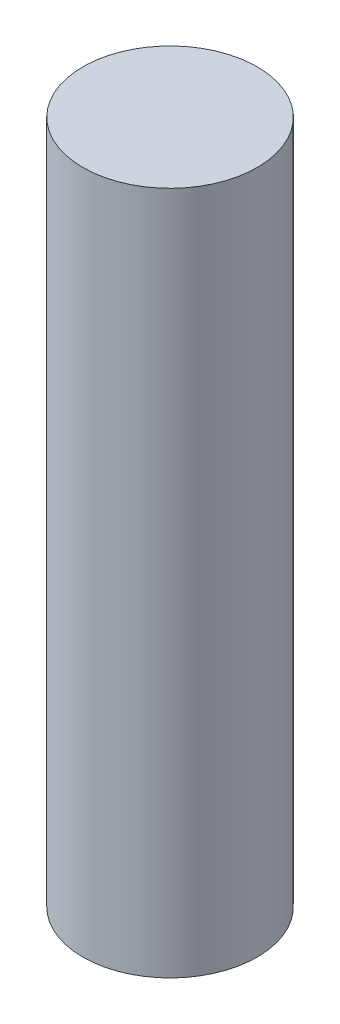
SolidWorks part; units mm, degrees
ref_plane "정면" through (0, 0, 0) normal (0, 0, 1) x (1, 0, 0)
ref_plane "윗면" through (0, 0, 0) normal (0, 1, 0) x (1, 0, 0)
ref_plane "우측면" through (0, 0, 0) normal (1, 0, 0) x (0, 0, -1)
sketch "스케치1" plane through (0, 0, 0) normal (0, 1, 0) x (1, 0, 0)
  circle A0 centre (0, 0) radius 2.55
  dimension "D1" = 5.1
extrude "보스-돌출1" add sketch "스케치1" along normal blind 20
